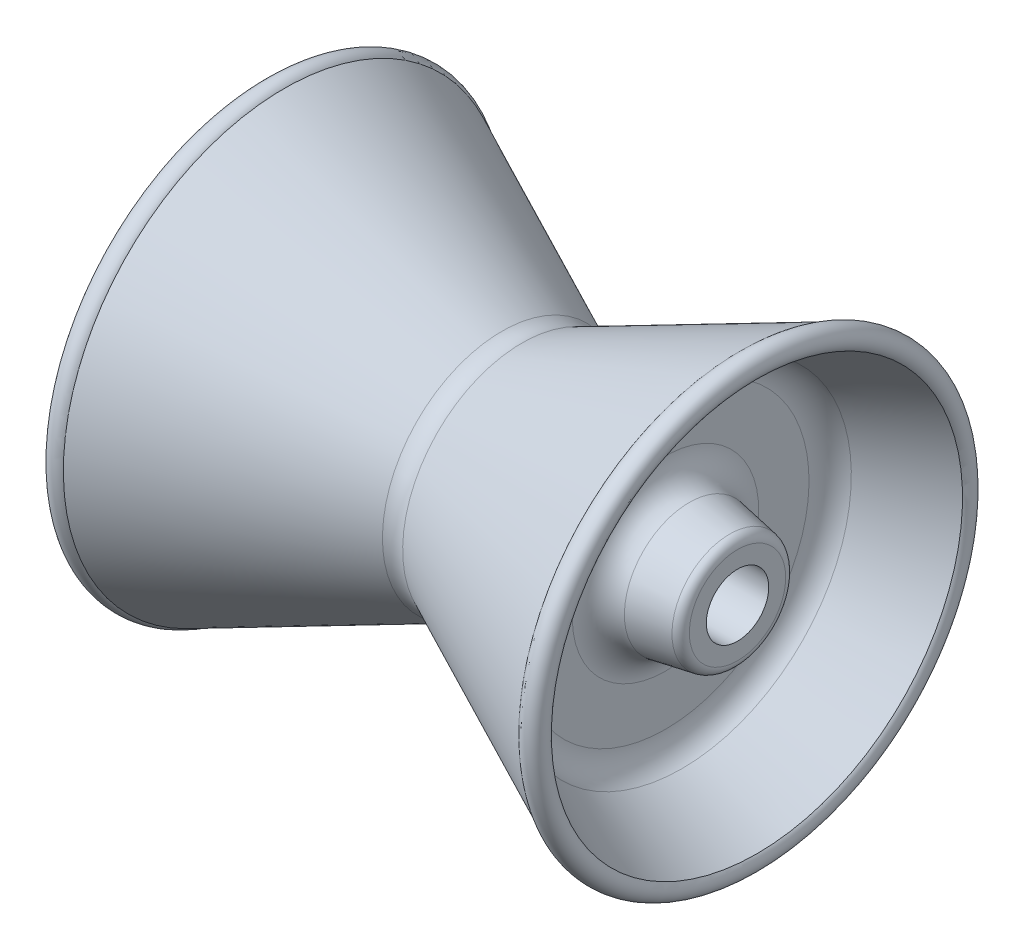
SolidWorks part; units mm, degrees
ref_plane "Front Plane" through (0, 0, 0) normal (0, 0, 1) x (1, 0, 0)
ref_plane "Top Plane" through (0, 0, 0) normal (0, 1, 0) x (1, 0, 0)
ref_plane "Right Plane" through (0, 0, 0) normal (1, 0, 0) x (0, 0, -1)
sketch "Sketch1" plane through (0, 0, 0) normal (0, 0, 1) x (1, 0, 0)
  line L0 (-235, 0) -> (235, 0) construction
  line L1 (0, 122.0334) -> (0, 97.0334) construction
  line L2 (-234.7892, 32.5) -> (-234.7892, 50.1555)
  line L3 (-226.546, 60) -> (-184.5188, 67.5)
  line L4 (-159.7892, 97.0334) -> (-159.7892, 149.4392)
  line L5 (-176.8008, 176.4818) -> (-255, 214.0405)
  line L6 (-130, 32.5) -> (-130, 106.314)
  line L7 (-87.0116, 133.3565) -> (-21.6473, 101.9624)
  line L8 (-234.7892, 32.5) -> (-130, 32.5)
  line L10 (87.0116, 133.3565) -> (21.6473, 101.9624)
  line L12 (234.7892, 32.5) -> (130, 32.5)
  line L13 (130, 32.5) -> (130, 106.314)
  line L14 (176.8008, 176.4818) -> (255, 214.0405)
  line L15 (159.7892, 97.0334) -> (159.7892, 149.4392)
  line L16 (226.546, 60) -> (184.5188, 67.5)
  line L17 (234.7892, 32.5) -> (234.7892, 50.1555)
  line L18 (-237.0773, 230) -> (-10.5223, 124.3557)
  line L19 (237.0773, 230) -> (10.5223, 124.3557)
  arc A1 (-226.546, 60) -> (-234.7892, 50.1555) centre (-224.7892, 50.1555) ccw
  arc A2 (-184.5188, 67.5) -> (-159.7892, 97.0334) centre (-189.7892, 97.0334) ccw
  arc A3 (-159.7892, 149.4392) -> (-176.8008, 176.4818) centre (-189.7892, 149.4392) ccw
  arc A4 (-87.0116, 133.3565) -> (-130, 106.314) centre (-100, 106.314) ccw
  arc A8 (-10.5223, 124.3557) -> (10.5223, 124.3557) centre (0, 147.0334) ccw
  arc A9 (-21.6473, 101.9624) -> (21.6473, 101.9624) centre (0, 147.0334) ccw
  arc A11 (87.0116, 133.3565) -> (130, 106.314) centre (100, 106.314) cw
  arc A12 (159.7892, 149.4392) -> (176.8008, 176.4818) centre (189.7892, 149.4392) cw
  arc A13 (184.5188, 67.5) -> (159.7892, 97.0334) centre (189.7892, 97.0334) cw
  arc A14 (226.546, 60) -> (234.7892, 50.1555) centre (224.7892, 50.1555) cw
  arc A15 (-237.0773, 230) -> (-255, 214.0405) centre (-246.1277, 222.1202) ccw
  arc A16 (237.0773, 230) -> (255, 214.0405) centre (246.1277, 222.1202) cw
  point P3 (0, 97.0334)
  point P5 (0, 0)
  point P28 (0, 139.7438)
  point P32 (-14.5853, 129.0842)
  point P36 (255, 209.404)
  dimension "D3" = 10
  dimension "D1" = 30
  dimension "D12" = 12
  dimension "D13" = 50
  dimension "D14" = 25
  dimension "D2" = 60
  dimension "D4" = 67.5
  dimension "D5" = 75
  dimension "D6" = 255
  dimension "D7" = 230
  dimension "D8" = 130
  dimension "D9" = 235
  dimension "D10" = 130
  dimension "D11" = 32.5
revolve "Revolve1" add sketch "Sketch1" angle 360 about L0
